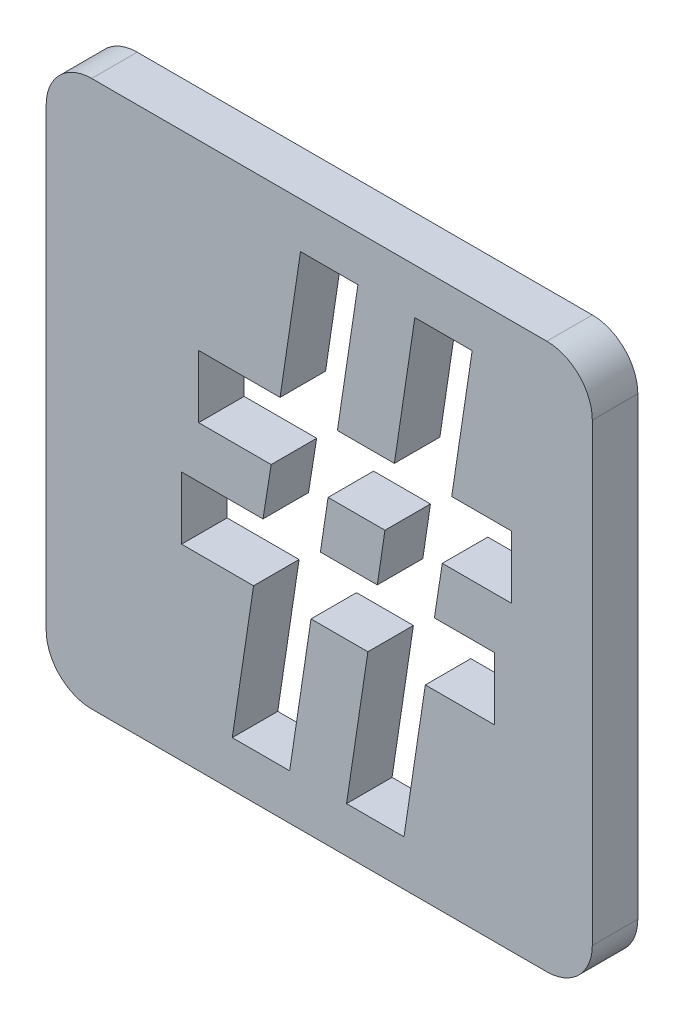
SolidWorks part; units mm, degrees
ref_plane "Front Plane" through (0, 0, 0) normal (0, 0, 1) x (1, 0, 0)
ref_plane "Top Plane" through (0, 0, 0) normal (0, 1, 0) x (1, 0, 0)
ref_plane "Right Plane" through (0, 0, 0) normal (1, 0, 0) x (0, 0, -1)
sketch "Sketch1" plane through (0, 0, 0) normal (0, 0, 1) x (1, 0, 0)
  line L1 (-50, 60) -> (50, 60)
  line L2 (-60, 50) -> (-60, -50)
  line L3 (-50, -60) -> (50, -60)
  line L4 (60, 50) -> (60, -50)
  line L5 (-60, 60) -> (60, -60) construction
  line L6 (-60, -60) -> (60, 60) construction
  arc A0 (-60, -50) -> (-50, -60) centre (-50, -50) ccw
  arc A1 (50, -60) -> (60, -50) centre (50, -50) ccw
  arc A2 (50, 60) -> (60, 50) centre (50, 50) cw
  arc A3 (-50, 60) -> (-60, 50) centre (-50, 50) ccw
  point P0 (0, 0)
  dimension "D3" = 10
  dimension "D1" = 120
  dimension "D2" = 120
extrude "Boss-Extrude1" add sketch "Sketch1" along normal blind 10 contours A3 L2 A0 L3 A1 L4 A2 L1
sketch "Sketch2" plane through (0, 0, 10) normal (0, 0, 1) x (1, 0, 0)
  line L0 (0, 0) -> (0, 40) construction
  line L1 (-50, 50) -> (50, 50) construction
  line L2 (-50, 50) -> (-50, -50) construction
  line L3 (-50, -50) -> (50, -50) construction
  line L4 (50, 50) -> (50, -50) construction
  line L5 (-50, 50) -> (50, -50) construction
  line L6 (-50, -50) -> (50, 50) construction
  line L7 (0, 40) -> (-40, 40) construction
  line L8 (-40, 40) -> (-40, 0) construction
  line L9 (-40, 0) -> (0, 0) construction
  line L11 (0, 20) -> (-20, 20) construction
  line L12 (-20, 40) -> (-20, 20) construction
  circle A0 centre (0, 40) radius 4 construction
  circle A1 centre (0, 20) radius 4 construction
  circle A2 centre (0, 0) radius 4 construction
  circle A3 centre (-20, 20) radius 4 construction
  circle A4 centre (-20, 40) radius 4 construction
  circle A5 centre (-40, 40) radius 4 construction
  circle A6 centre (0, 0) radius 4 construction
  circle A7 centre (20, 0) radius 4 construction
  circle A8 centre (40, 0) radius 4 construction
  circle A9 centre (40, 20) radius 4 construction
  circle A10 centre (40, 40) radius 4 construction
  circle A11 centre (20, 20) radius 4 construction
  circle A12 centre (0, 0) radius 4 construction
  circle A13 centre (0, -20) radius 4 construction
  circle A14 centre (0, -40) radius 4 construction
  circle A15 centre (20, -40) radius 4 construction
  circle A16 centre (40, -40) radius 4 construction
  circle A17 centre (20, -20) radius 4 construction
  circle A18 centre (0, 0) radius 4 construction
  circle A19 centre (-20, 0) radius 4 construction
  circle A20 centre (-40, 0) radius 4 construction
  circle A21 centre (-40, -20) radius 4 construction
  circle A22 centre (-40, -40) radius 4 construction
  circle A23 centre (-20, -20) radius 4 construction
  text T0 "#" font "Century Gothic" height 97.5
  point P0 (0, 0)
  point P55 (0, 0)
  dimension "D4" = 8
  dimension "D1" = 100
  dimension "D2" = 100
  dimension "D3" = 40
  dimension "D5" = 4
extrude "Cut-Extrude11" cut sketch "Sketch2" against normal blind 10
